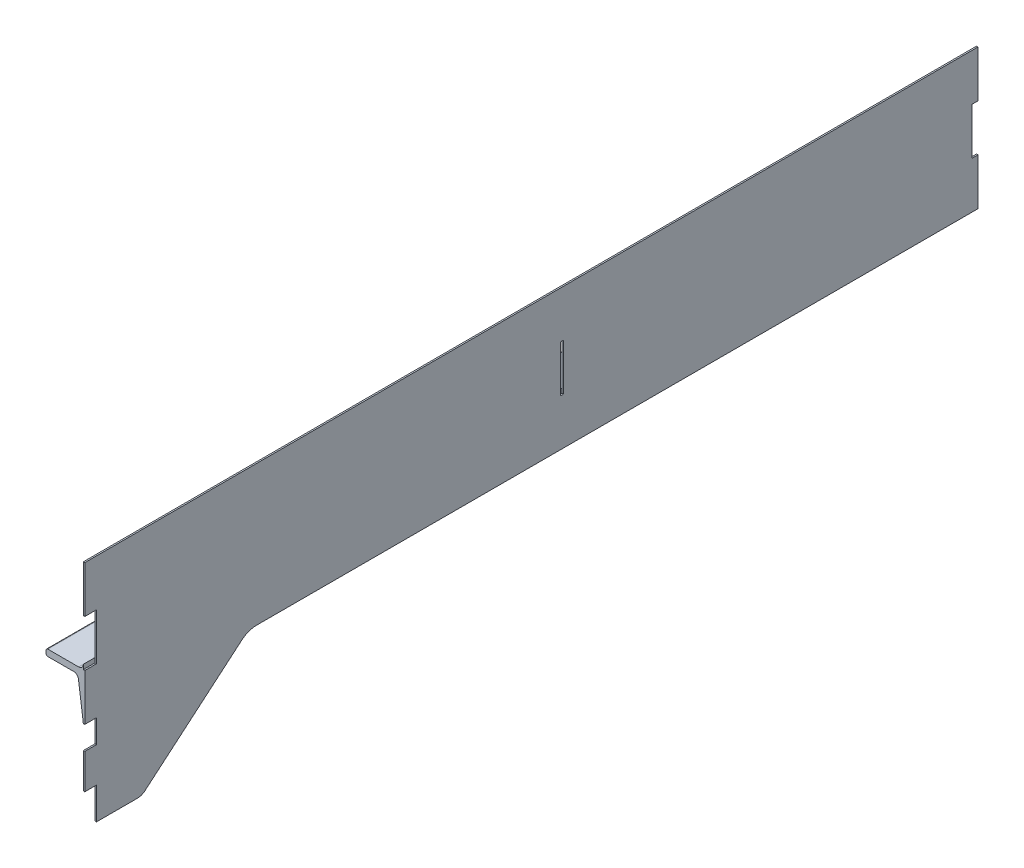
SolidWorks part; units mm, degrees
material "S-Glass Fiber"
ref_plane "Front Plane" through (0, 0, 0) normal (0, 0, 1) x (1, 0, 0)
ref_plane "Top Plane" through (0, 0, 0) normal (0, 1, 0) x (1, 0, 0)
ref_plane "Right Plane" through (0, 0, 0) normal (1, 0, 0) x (0, 0, -1)
ref_plane "Plane1" through (-94.488, 0, 0) normal (-1, 0, 0) x (0, -1, 0)
sketch "Sketch1" plane through (-94.488, 0, 0) normal (-1, 0, 0) x (0, -1, 0)
  line L0 (111.125, -457.2) -> (85.725, -457.2)
  line L1 (85.725, -457.2) -> (85.725, -455.6125)
  line L2 (85.725, -455.6125) -> (111.125, -455.6125)
  line L3 (111.125, -455.6125) -> (111.125, -457.2)
  line L4 (111.125, -203.2) -> (85.725, -203.2)
  line L5 (85.725, -203.2) -> (85.725, -196.85)
  line L6 (85.725, -196.85) -> (60.325, -196.85)
  line L7 (60.325, -196.85) -> (60.325, -682.625)
  line L8 (60.325, -682.625) -> (85.725, -682.625)
  line L9 (85.725, -682.625) -> (85.725, -679.45)
  line L10 (85.725, -679.45) -> (111.125, -679.45)
  line L11 (111.125, -679.45) -> (111.125, -682.625)
  line L12 (111.125, -682.625) -> (136.525, -682.625)
  line L13 (136.525, -682.625) -> (136.525, -196.85)
  line L14 (136.525, -196.85) -> (111.125, -196.85)
  line L15 (111.125, -196.85) -> (111.125, -203.2)
  line L16 (136.525, -196.85) -> (185.6232, -196.85) construction
  line L17 (185.6232, -196.85) -> (185.6232, -227.7965) construction
  line L18 (184.1182, -229.5729) -> (139.535, -282.1971)
  line L19 (136.525, -203.2) -> (149.225, -203.2)
  line L20 (149.225, -203.2) -> (149.225, -196.85)
  line L21 (168.275, -196.85) -> (168.275, -203.2)
  line L22 (168.275, -203.2) -> (185.6232, -203.2)
  line L23 (185.6232, -203.2) -> (185.6232, -225.4683)
  line L24 (168.275, -196.85) -> (149.225, -196.85)
  circle A0 centre (130.175, -666.75) radius 1.7526 construction
  circle A1 centre (130.175, -615.95) radius 1.7526 construction
  circle A2 centre (130.175, -565.15) radius 1.7526 construction
  circle A3 centre (130.175, -514.35) radius 1.7526 construction
  circle A4 centre (130.175, -463.55) radius 1.7526 construction
  circle A5 centre (130.175, -412.75) radius 1.7526 construction
  circle A6 centre (130.175, -361.95) radius 1.7526 construction
  circle A7 centre (130.175, -311.15) radius 1.7526 construction
  circle A8 centre (130.175, -260.35) radius 1.7526 construction
  circle A9 centre (130.175, -209.55) radius 1.7526 construction
  arc A10 (184.1182, -229.5729) -> (185.6232, -225.4683) centre (179.2732, -225.4683) ccw
  arc A11 (139.535, -282.1971) -> (136.525, -290.4065) centre (149.225, -290.4065) ccw
  point P38 (136.525, -285.75)
  dimension "D14" = 12.7
  dimension "D15" = 6.35
  dimension "D1" = 222.25
  dimension "D2" = 485.775
  dimension "D3" = 76.2
  dimension "D4" = 3.175
  dimension "D5" = 6.35
  dimension "D6" = 25.4
  dimension "D7" = 25.4
  dimension "D8" = 1.5875
  dimension "D9" = 49.0982
  dimension "D10" = 82.55
  dimension "D11" = 40.271
  dimension "D12" = 19.05
  dimension "D13" = 12.7
extrude "Boss-Extrude1" add sketch "Sketch1" against normal blind 0.7937
sketch "Sketch4" plane through (0, 0, -679.45) normal (0, 0, -1) x (-1, 0, 0)
  line L0 (97.1661, -116.8229) -> (94.488, -136.525)
  line L1 (97.028, -111.125) -> (113.7935, -111.125)
  line L2 (94.488, -111.125) -> (94.488, -114.2531)
  line L3 (99.683, -114.625) -> (113.7935, -114.625)
  line L4 (114.7935, -112.125) -> (114.7935, -113.625)
  line L5 (94.488, -136.525) -> (94.488, -114.2531)
  line L10 (94.488, -111.125) -> (94.488, -108.585)
  arc A0 (97.1661, -116.8229) -> (99.683, -114.625) centre (99.683, -117.165) cw
  arc A1 (94.488, -108.585) -> (97.028, -111.125) centre (97.028, -108.585) ccw
  arc A2 (113.7935, -114.625) -> (114.7935, -113.625) centre (113.7935, -113.625) ccw
  arc A3 (113.7935, -111.125) -> (114.7935, -112.125) centre (113.7935, -112.125) cw
  point P9 (97.4649, -114.625)
  dimension "D3" = 2.54
  dimension "D4" = 2.54
  dimension "D1" = 1
  dimension "D2" = 3
extrude "Boss-Extrude2" add sketch "Sketch4" against normal blind 482.6
